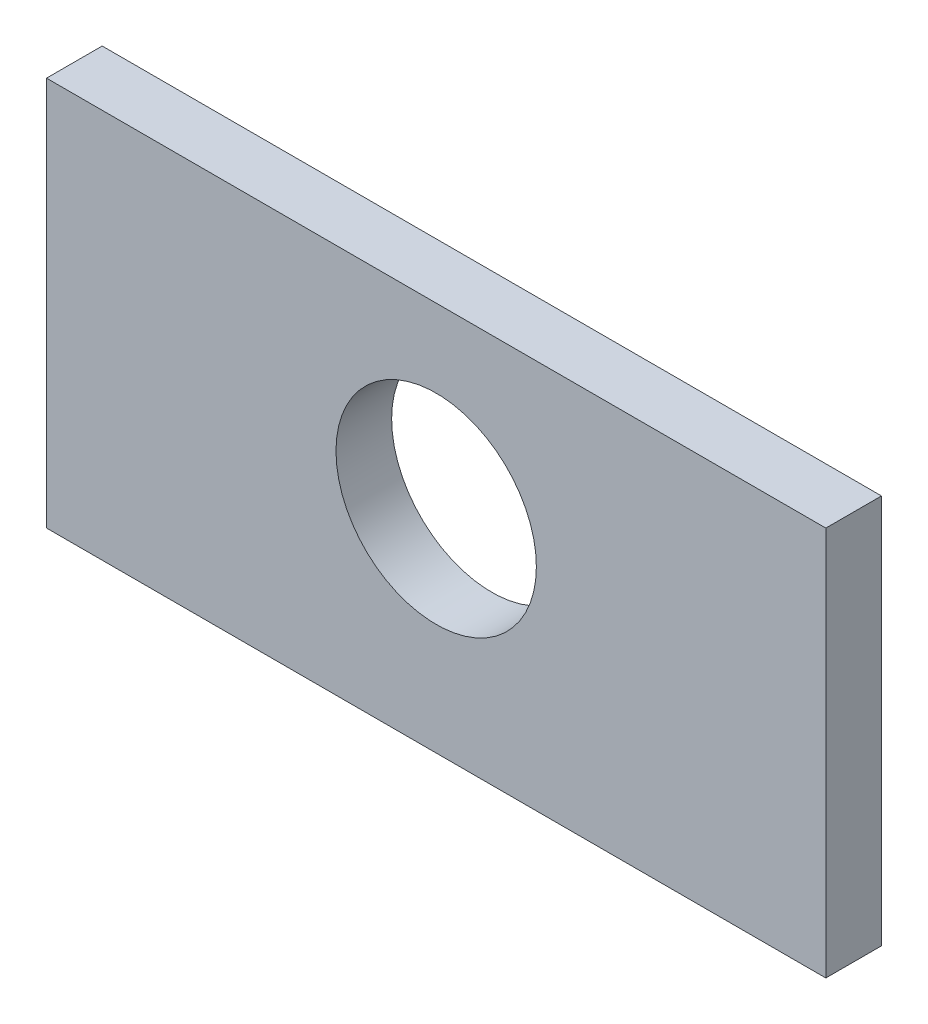
SolidWorks part; units mm, degrees
material "AISI 304"
ref_plane "Спереди" through (0, 0, 0) normal (0, 0, 1) x (1, 0, 0)
ref_plane "Сверху" through (0, 0, 0) normal (0, 1, 0) x (1, 0, 0)
ref_plane "Справа" through (0, 0, 0) normal (1, 0, 0) x (0, 0, -1)
sketch "Эскиз1" plane through (0, 0, 0) normal (0, 0, 1) x (1, 0, 0)
  line L0 (0, 0) -> (0, 3) construction
  line L1 (-70, -35) -> (70, -35)
  line L2 (-70, -35) -> (-70, 35)
  line L3 (-70, 35) -> (70, 35)
  line L4 (70, -35) -> (70, 35)
  line L5 (-70, -35) -> (70, 35) construction
  line L6 (-70, 35) -> (70, -35) construction
  circle A1 centre (0, 3) radius 18
  point P7 (0, 0)
  dimension "D3" = 36
  dimension "D4" = 38
  dimension "D1" = 140
  dimension "D2" = 70
extrude "Бобышка-Вытянуть1" add sketch "Эскиз1" along normal mid plane 10
sketch "Эскиз2" plane through (0, 0, -5) normal (0, 0, -1) x (-1, 0, 0)
  circle A0 centre (0, 0) radius 17
  dimension "D1" = 34
split line "Разделяющая линия1" [suppressed]
